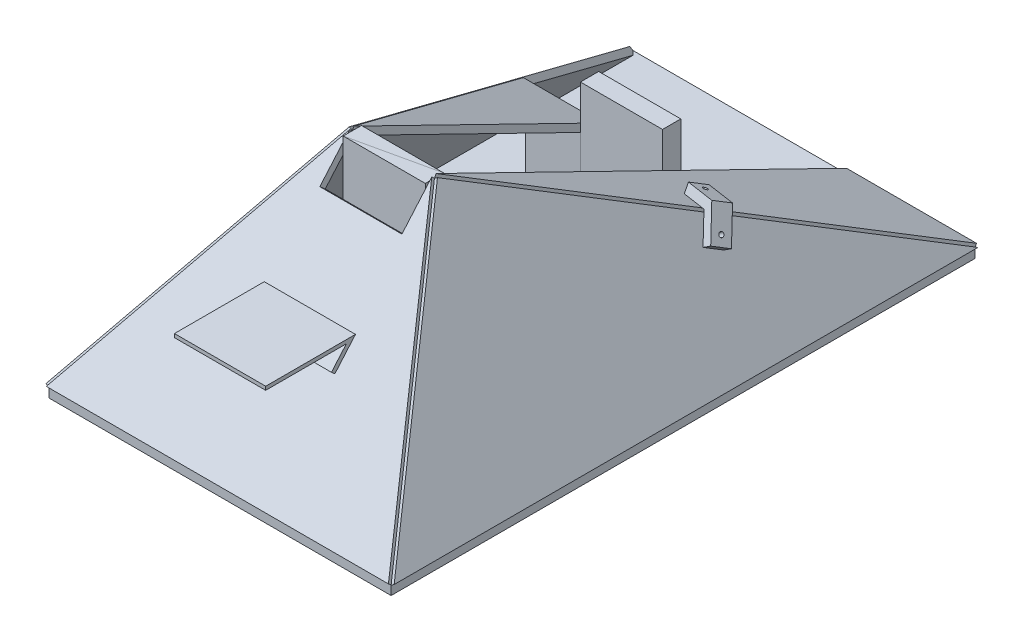
SolidWorks part; units mm, degrees
other "PlasticMountC"
other "PlasticMountB"
other "PlasticMountA"
other "PlasticMountG"
other "PlasticMountF"
other "PlasticMountE"
other "Cube Mount"
other "PlasticMountD"
other "PlasticMountH"
ref_plane "Front Plane" through (0, 0, 0) normal (0, 0, 1) x (1, 0, 0)
ref_plane "Top Plane" through (0, 0, 0) normal (0, 1, 0) x (1, 0, 0)
ref_plane "Right Plane" through (0, 0, 0) normal (1, 0, 0) x (0, 0, -1)
sketch "Sketch1" plane through (0, 0, 0) normal (0, 1, 0) x (1, 0, 0)
  line L1 (238.125, -406.4) -> (-238.125, -406.4)
  line L2 (238.125, -406.4) -> (238.125, 406.4)
  line L3 (238.125, 406.4) -> (-238.125, 406.4)
  line L4 (-238.125, -406.4) -> (-238.125, 406.4)
  line L5 (238.125, -406.4) -> (-238.125, 406.4) construction
  line L6 (238.125, 406.4) -> (-238.125, -406.4) construction
  point P0 (0, 0)
  dimension "D1" = 476.25
  dimension "D2" = 812.8
ref_plane "Plane1" through (0, 279.4, 0) normal (0, 1, 0) x (1, 0, 0)
sketch "Sketch2" plane through (0, 279.4, 0) normal (0, 1, 0) x (1, 0, 0)
  line L0 (0, 0) -> (0, -165.1) construction
  line L1 (238.125, -406.4) -> (-238.125, -406.4) construction
  line L2 (-57.15, -177.8) -> (57.15, -177.8)
  line L3 (-57.15, -177.8) -> (-57.15, -152.4)
  line L4 (-57.15, -152.4) -> (57.15, -152.4)
  line L5 (57.15, -177.8) -> (57.15, -152.4)
  line L6 (-57.15, -177.8) -> (57.15, -152.4) construction
  line L7 (-57.15, -152.4) -> (57.15, -177.8) construction
  line L8 (57.15, -165.1) -> (-57.15, -165.1) construction
  line L9 (0, 0) -> (0, 165.1) construction
  line L11 (-57.15, 152.4) -> (57.15, 152.4)
  line L12 (-57.15, 152.4) -> (-57.15, 177.8)
  line L13 (-57.15, 177.8) -> (57.15, 177.8)
  line L14 (57.15, 152.4) -> (57.15, 177.8)
  line L15 (-57.15, 152.4) -> (57.15, 177.8) construction
  line L16 (-57.15, 177.8) -> (57.15, 152.4) construction
  dimension "D1" = 114.3
  dimension "D2" = 25.4
  dimension "D3" = 228.6
  dimension "D4" = 558.8
ref_plane "Plane2" through (167.7467, 108.6541, 0) normal (0.8393, 0.5436, 0) x (0, 0, -1)
ref_plane "Plane3" through (-167.7467, 108.6541, 0) normal (-0.8393, 0.5436, 0) x (0, 0, 1)
sketch "Sketch4" plane through (167.7467, 108.6541, 0) normal (0.8393, 0.5436, 0) x (0, 0, -1)
  line L0 (-406.4, -129.4559) -> (-165.1, 203.435)
  line L2 (-165.1, 203.435) -> (406.4, -129.4559)
  line L3 (406.4, -129.4559) -> (-406.4, -129.4559)
extrude "Boss-Extrude1" add sketch "Sketch4" along normal mid plane 10
sketch "Sketch5" plane through (-167.7467, 108.6541, 0) normal (-0.8393, 0.5436, 0) x (0, 0, 1)
  line L0 (165.1, 203.435) -> (-406.4, -129.4559)
  line L1 (-406.4, -129.4559) -> (406.4, -129.4559)
  line L2 (406.4, -129.4559) -> (165.1, 203.435)
extrude "Boss-Extrude2" add sketch "Sketch5" along normal mid plane 10
extrude "Boss-Extrude3" add sketch "Sketch2" against normal up to vertex (279.4 mm away) separate body up to point (238.125, 0, 406.4)
sketch "Sketch6" plane through (0, 0, 177.8) normal (0, 0, 1) x (1, 0, 0)
  line L0 (57.15, 152.5607) -> (57.15, 177.9607)
  line L1 (57.15, 0) -> (57.15, 279.4) construction
  line L2 (57.15, 177.9607) -> (116.8977, 177.9607)
  line L3 (52.9534, 276.6818) -> (233.9284, -2.7182) construction
  line L4 (116.8977, 177.9607) -> (133.35, 152.5607)
  line L5 (133.35, 152.5607) -> (57.15, 152.5607)
  dimension "D1" = 25.4
  dimension "D2" = 76.2
extrude "Boss-Extrude4" add sketch "Sketch6" against normal blind 25.4 separate body
ref_plane "Plane4" through (133.35, 0, 0) normal (1, 0, 0) x (0, 0, -1)
hole_wizard "CBORE for 1/4 Binding Head Machine Screw1" positions "Sketch7" profile "Sketch9" counterbore size "1/4" standard "ANSI Inch" end condition through all
sketch "Sketch7" plane through (133.35, 0, 0) normal (1, 0, 0) x (0, 0, -1)
  line L0 (-177.8, 165.2607) -> (-165.1, 165.2607) construction
  line L1 (-177.8, 152.5607) -> (-177.8, 177.9607) construction
  line L2 (-165.1, 165.2607) -> (-152.4, 165.2607) construction
  line L3 (-152.4, 152.5607) -> (-152.4, 177.9607) construction
  point P0 (-165.1, 165.2607)
sketch "Sketch9" plane through (133.35, 165.2607, 165.1) normal (0, 1, 0) x (0, 0, -1)
  line L0 (0, 0) -> (0, 375.6716)
  line L1 (0, 375.6716) -> (3.3782, 375.6716)
  line L3 (3.3782, 375.6716) -> (3.3782, 54.191)
  line L4 (3.3782, 54.191) -> (7.1437, 54.191)
  line L5 (7.1437, 54.191) -> (7.1437, 0)
  line L7 (7.1437, 0) -> (0, 0)
  line L11 (0, -6.35) -> (0, 107.95) construction
  dimension "Thru Hole Dia." = 6.7564
  dimension "Thru Hole Depth" = 375.6716
  dimension "C'Bore Dia." = 14.2875
  dimension "C'Bore Depth" = 54.191
extrude "Boss-Extrude5" add sketch "Sketch1" against normal blind 12.7
sketch "Sketch10" plane through (0, 0, 177.8) normal (0, 0, 1) x (1, 0, 0)
  line L0 (182.8109, 0) -> (208.2109, 0)
  line L1 (-238.125, 0) -> (238.125, 0) construction
  line L2 (208.2109, 0) -> (208.2109, 36.986)
  line L3 (52.9534, 276.6818) -> (233.9284, -2.7182) construction
  line L4 (208.2109, 36.986) -> (182.8109, 76.2)
  line L5 (182.8109, 76.2) -> (182.8109, 0)
  dimension "D1" = 25.4
  dimension "D2" = 76.2
extrude "Boss-Extrude6" add sketch "Sketch10" along normal blind 25.4 separate body
ref_plane "Plane5" through (0, 76.2, 0) normal (0, 1, 0) x (1, 0, 0)
hole_wizard "CBORE for 1/4 Binding Head Machine Screw2" positions "Sketch11" profile "Sketch12" counterbore size "1/4" standard "ANSI Inch" end condition through all
sketch "Sketch11" plane through (0, 76.2, 0) normal (0, 1, 0) x (1, 0, 0)
  line L0 (182.8109, -190.5) -> (195.5109, -190.5) construction
  line L1 (182.8109, -203.2) -> (182.8109, -177.8) construction
  line L2 (195.5109, -190.5) -> (208.2109, -190.5) construction
  line L3 (208.2109, -203.2) -> (208.2109, -177.8) construction
  point P0 (195.5109, -190.5)
sketch "Sketch12" plane through (195.5109, 76.2, 190.5) normal (1, 0, 0) x (0, 0, 1)
  line L0 (0, 0) -> (0, 88.9)
  line L1 (0, 88.9) -> (3.3782, 88.9)
  line L3 (3.3782, 88.9) -> (3.3782, 64.191)
  line L4 (3.3782, 64.191) -> (7.1437, 64.191)
  line L5 (7.1437, 64.191) -> (7.1437, 0)
  line L7 (7.1437, 0) -> (0, 0)
  line L11 (0, -6.35) -> (0, 107.95) construction
  dimension "Thru Hole Dia." = 6.7564
  dimension "Thru Hole Depth" = 88.9
  dimension "C'Bore Dia." = 14.2875
  dimension "C'Bore Depth" = 64.191
mirror "Mirror2" about plane through (0, 0, 0) normal (1, 0, 0) of bodies 108
other "Move Face1" face at (-195.5109, 12.009, 193.8782) face at (-192.1327, 0, 190.5) parameters "D1"=6.35
ref_plane "Plane6" through (0, 201.0357, 232.7782) normal (0, 0.6536, 0.7568) x (1, 0, 0)
ref_plane "Plane7" through (0, 160.3571, -78.3968) normal (0, -0.8984, 0.4392) x (-1, 0, 0)
sketch "Sketch14" plane through (0, 201.0357, 232.7782) normal (0, 0.6536, 0.7568) x (1, 0, 0)
  line L0 (-57.15, 103.5437) -> (-238.125, -265.6311)
  line L1 (-238.125, -265.6311) -> (238.125, -265.6311)
  line L2 (238.125, -265.6311) -> (57.15, 103.5437)
  line L3 (57.15, 103.5437) -> (57.15, 40.0437)
  line L4 (57.15, 40.0437) -> (-57.15, 40.0437)
  line L5 (-57.15, 40.0437) -> (-57.15, 103.5437)
  dimension "D1" = 63.5
extrude "Boss-Extrude7" add sketch "Sketch14" along normal mid plane 10 separate body
sketch "Sketch15" plane through (0, 160.3571, -78.3968) normal (0, -0.8984, 0.4392) x (-1, 0, 0)
  line L0 (-57.15, -271.0386) -> (-57.15, 365.1034)
  line L1 (-238.125, 365.1034) -> (238.125, 365.1034) construction
  line L2 (-57.15, 365.1034) -> (-238.125, 365.1034)
  line L3 (-238.125, 365.1034) -> (-57.15, -271.0386)
extrude "Boss-Extrude8" add sketch "Sketch15" along normal mid plane 10 separate body
sketch "Sketch16" plane through (57.15, 0, 0) normal (1, 0, 0) x (0, 0, -1)
  line L0 (-177.8, 194.2135) -> (-177.8, 168.8135)
  line L1 (-177.8, 0) -> (-177.8, 279.4) construction
  line L2 (-177.8, 168.8135) -> (-254, 168.8135)
  line L3 (-402.6159, -3.2681) -> (-161.3159, 276.1319) construction
  line L4 (-254, 168.8135) -> (-232.0636, 194.2135)
  line L5 (-232.0636, 194.2135) -> (-177.8, 194.2135)
  dimension "D1" = 25.4
  dimension "D2" = 76.2
extrude "Boss-Extrude9" add sketch "Sketch16" against normal blind 25.4 separate body
ref_plane "Plane8" through (0, 0, 254) normal (0, 0, 1) x (1, 0, 0)
hole_wizard "CBORE for 1/4 Binding Head Machine Screw3" positions "Sketch19" profile "Sketch20" counterbore size "1/4" standard "ANSI Inch" end condition through all
sketch "Sketch19" plane through (0, 0, 254) normal (0, 0, 1) x (1, 0, 0)
  line L0 (44.45, 181.5135) -> (31.75, 181.5135) construction
  line L1 (31.75, 194.2135) -> (31.75, 168.8135) construction
  line L4 (44.45, 181.5135) -> (57.15, 181.5135) construction
  line L5 (57.15, 194.2135) -> (57.15, 168.8135) construction
  point P0 (44.45, 181.5135)
sketch "Sketch20" plane through (44.45, 181.5135, 254) normal (1, 0, 0) x (0, -1, 0)
  line L0 (0, 0) -> (0, 662.5961)
  line L1 (0, 662.5961) -> (3.3782, 662.5961)
  line L3 (3.3782, 662.5961) -> (3.3782, 64.191)
  line L4 (3.3782, 64.191) -> (7.1437, 64.191)
  line L5 (7.1437, 64.191) -> (7.1437, 0)
  line L7 (7.1437, 0) -> (0, 0)
  line L11 (0, -6.35) -> (0, 107.95) construction
  dimension "Thru Hole Dia." = 6.7564
  dimension "Thru Hole Depth" = 662.5961
  dimension "C'Bore Dia." = 14.2875
  dimension "C'Bore Depth" = 64.191
sketch "Sketch21" plane through (0, 0, 0) normal (1, 0, 0) x (0, 0, -1)
  line L0 (-406.4, 147.4) -> (-294.0969, 147.4)
  line L1 (-410.1841, 3.2681) -> (-168.8841, 282.6681) construction
  line L2 (-406.4, 147.4) -> (-406.4, 0) construction
  line L3 (-410.1841, 3.2681) -> (-402.6159, -3.2681) construction
  line L4 (-406.4, 147.4) -> (-406.4, 152.4)
  line L5 (-406.4, 152.4) -> (-281.3884, 152.4)
  line L7 (-281.3884, 152.4) -> (-310.0435, 119.2204)
  line L8 (-310.0435, 119.2204) -> (-314.8493, 123.3709)
  line L9 (-314.8493, 123.3709) -> (-294.0969, 147.4)
  line L10 (406.4, 0) -> (-406.4, 0) construction
  dimension "D1" = 5
  dimension "D2" = 31.75
  dimension "D3" = 6.35
  dimension "D4" = 152.4
extrude "Boss-Extrude10" add sketch "Sketch21" along normal mid plane 127 separate body
sketch "Sketch22" plane through (0, 208.4543, 241.3682) normal (0, 0.6536, 0.7568) x (1, 0, 0)
  line L0 (-63.5, -99.7219) -> (63.5, -99.7219) construction
  line L3 (-63.5, -80.6719) -> (-63.5, -112.4219) construction
  line L4 (63.5, -80.6719) -> (63.5, -112.4219) construction
  line L5 (63.5, -112.4219) -> (-63.5, -112.4219) construction
  line L6 (-35.1275, -93.8719) -> (-38.505, -99.7219)
  line L7 (-38.505, -99.7219) -> (-35.1275, -105.5719)
  line L8 (-35.1275, -105.5719) -> (-28.3725, -105.5719)
  line L9 (-28.3725, -105.5719) -> (-24.995, -99.7219)
  line L10 (-24.995, -99.7219) -> (-28.3725, -93.8719)
  line L11 (-28.3725, -93.8719) -> (-35.1275, -93.8719)
  line L12 (35.1275, -93.8719) -> (28.3725, -93.8719)
  line L13 (28.3725, -93.8719) -> (24.995, -99.7219)
  line L14 (24.995, -99.7219) -> (28.3725, -105.5719)
  line L15 (28.3725, -105.5719) -> (35.1275, -105.5719)
  line L16 (35.1275, -105.5719) -> (38.505, -99.7219)
  line L17 (38.505, -99.7219) -> (35.1275, -93.8719)
  circle A0 centre (-31.75, -99.7219) radius 5.85 construction
  circle A1 centre (31.75, -99.7219) radius 5.85 construction
  dimension "D4" = 11.7
  dimension "D1" = 12.7
  dimension "D2" = 31.75
  dimension "D3" = 31.75
extrude "Cut-Extrude1" cut sketch "Sketch22" against normal blind 3
hole_wizard "1/4 (0.25) Diameter Hole1" positions "Sketch24" profile "Sketch26" hole size "1/4" standard "ANSI Inch" end condition through all
sketch "Sketch24" plane through (0, 206.4935, 239.0977) normal (0, 0.6536, 0.7568) x (1, 0, 0)
  line L0 (-35.1275, -93.8719) -> (-28.3725, -105.5719) construction
  line L1 (24.995, -99.7219) -> (38.505, -99.7219) construction
  point P7 (-31.75, -99.7219)
  point P16 (31.75, -99.7219)
sketch "Sketch26" plane through (31.75, 131.0217, 304.2779) normal (1, 0, 0) x (0, -0.7568, 0.6536)
  line L0 (0, 0) -> (0, 631.7967)
  line L1 (0, 631.7967) -> (3.175, 631.7967)
  line L2 (3.175, 631.7967) -> (3.175, 0)
  line L5 (3.175, 0) -> (0, 0)
  line L11 (0, -6.35) -> (0, 107.95) construction
  dimension "Thru Hole Dia." = 6.35
  dimension "Thru Hole Depth" = 631.7967
sketch "Sketch27" plane through (57.15, 0, 0) normal (1, 0, 0) x (0, 0, -1)
  line L0 (-152.4, 217.9545) -> (-50.8, 217.9545)
  line L1 (-152.4, 0) -> (-152.4, 279.4) construction
  line L2 (404.2039, -4.4919) -> (-167.2961, 274.9081) construction
  line L3 (-50.8, 217.9545) -> (-102.7545, 243.3545)
  line L4 (-102.7545, 243.3545) -> (-152.4, 243.3545)
  line L5 (-152.4, 243.3545) -> (-152.4, 217.9545)
  dimension "D1" = 25.4
  dimension "D2" = 101.6
extrude "Boss-Extrude11" add sketch "Sketch27" along normal blind 25.4 separate body
ref_plane "Plane9" through (0, 0, 50.8) normal (0, 0, -1) x (-1, 0, 0)
hole_wizard "CBORE for 1/4 Binding Head Machine Screw4" positions "Sketch28" profile "Sketch30" counterbore size "1/4" standard "ANSI Inch" end condition through all
sketch "Sketch28" plane through (0, 0, 50.8) normal (0, 0, -1) x (-1, 0, 0)
  line L0 (-69.85, 243.3545) -> (-69.85, 217.9545) construction
  line L1 (-82.55, 243.3545) -> (-57.15, 243.3545) construction
  line L2 (-82.55, 217.9545) -> (-57.15, 217.9545) construction
  point P0 (-69.85, 230.6545)
sketch "Sketch30" plane through (69.85, 230.6545, 50.8) normal (1, 0, 0) x (0, 1, 0)
  line L0 (0, 0) -> (0, 359.3841)
  line L1 (0, 359.3841) -> (3.3782, 359.3841)
  line L3 (3.3782, 359.3841) -> (3.3782, 74.191)
  line L4 (3.3782, 74.191) -> (7.1437, 74.191)
  line L5 (7.1437, 74.191) -> (7.1437, 0)
  line L7 (7.1437, 0) -> (0, 0)
  line L11 (0, -6.35) -> (0, 107.95) construction
  dimension "Thru Hole Dia." = 6.7564
  dimension "Thru Hole Depth" = 359.3841
  dimension "C'Bore Dia." = 14.2875
  dimension "C'Bore Depth" = 74.191
sketch "Sketch31" plane through (57.15, 0, 0) normal (1, 0, 0) x (0, 0, -1)
  line L0 (177.8, 0) -> (177.8, 106.1945)
  line L1 (-406.4, 0) -> (406.4, 0) construction
  line L2 (404.2039, -4.4919) -> (-167.2961, 274.9081) construction
  line L3 (177.8, 106.1945) -> (152.4, 118.6122)
  line L4 (152.4, 118.6122) -> (152.4, 0)
  line L5 (152.4, 0) -> (177.8, 0)
  line L6 (177.8, 0) -> (177.8, 279.4) construction
  line L7 (152.4, 0) -> (177.8, 0) construction
extrude "Boss-Extrude12" add sketch "Sketch31" along normal blind 25.4 separate body
ref_plane "Plane10" through (0, 118.6122, 0) normal (0, 1, 0) x (1, 0, 0)
hole_wizard "CBORE for 1/4 Binding Head Machine Screw5" positions "Sketch32" profile "Sketch33" counterbore size "1/4" standard "ANSI Inch" end condition through all
sketch "Sketch32" plane through (0, 118.6122, 0) normal (0, 1, 0) x (1, 0, 0)
  line L0 (69.85, 177.8) -> (69.85, 152.4) construction
  line L1 (82.55, 177.8) -> (57.15, 177.8) construction
  line L2 (82.55, 152.4) -> (57.15, 152.4) construction
  point P8 (69.85, 165.1)
sketch "Sketch33" plane through (69.85, 118.6122, -165.1) normal (1, 0, 0) x (0, 0, 1)
  line L0 (0, 0) -> (0, 131.3122)
  line L1 (0, 131.3122) -> (3.3782, 131.3122)
  line L3 (3.3782, 131.3122) -> (3.3782, 94.191)
  line L4 (3.3782, 94.191) -> (7.1437, 94.191)
  line L5 (7.1437, 94.191) -> (7.1437, 0)
  line L7 (7.1437, 0) -> (0, 0)
  line L11 (0, -6.35) -> (0, 107.95) construction
  dimension "Thru Hole Dia." = 6.7564
  dimension "Thru Hole Depth" = 131.3122
  dimension "C'Bore Dia." = 14.2875
  dimension "C'Bore Depth" = 94.191
mirror "Mirror3" about plane through (0, 0, 0) normal (1, 0, 0) of bodies 123
other "Move Face2" face at (-69.85, 0, -161.7218) parameters "D1"=6.35
other "Move Face3" face at (-82.55, 59.3767, -165.1) parameters "D1"=50.8
ref_plane "Plane11" through (113.92, -175.8765, -359.7475) normal (0.2736, -0.4224, -0.8641) x (0, 0.8984, -0.4392)
sketch "Sketch36" plane through (113.92, -175.8765, -359.7475) normal (0.2736, -0.4224, -0.8641) x (0, 0.8984, -0.4392)
  line L0 (183.495, 93.9648) -> (183.495, 132.0648)
  line L1 (183.495, -44.9347) -> (183.495, 129.1334) construction
  line L2 (183.495, 132.0648) -> (150.2483, 150.6729)
  line L3 (-176.053, 333.3035) -> (180.937, 133.4965) construction
  line L4 (150.2483, 150.6729) -> (156.451, 161.7552)
  line L5 (156.451, 161.7552) -> (196.195, 139.5105)
  line L6 (196.195, 139.5105) -> (196.195, 93.9648)
  line L7 (196.195, 93.9648) -> (183.495, 93.9648)
  dimension "D1" = 12.7
  dimension "D2" = 38.1
extrude "Boss-Extrude13" add sketch "Sketch36" against normal blind 25.4 from offset 310 separate body offset against normal yes
hole_wizard "1/4 (0.25) Diameter Hole2" positions "Sketch39" profile "Sketch40" hole size "1/4" standard "ANSI Inch" end condition through all
sketch "Sketch39" plane through (0, 176.2585, -86.1708) normal (0, 0.8984, -0.4392) x (1, 0, 0)
  line L0 (128.2132, 60.8674) -> (115.9979, 64.3425) construction
  line L1 (112.5228, 52.1272) -> (119.4731, 76.5578) construction
  point P0 (128.2132, 60.8674)
  dimension "D1" = 12.7
sketch "Sketch40" plane through (128.2132, 149.5249, -140.8532) normal (1, 0, 0) x (0, 0.4392, 0.8984)
  line L0 (0, 0) -> (0, 386.0995)
  line L1 (0, 386.0995) -> (3.175, 386.0995)
  line L2 (3.175, 386.0995) -> (3.175, 0)
  line L5 (3.175, 0) -> (0, 0)
  line L11 (0, -6.35) -> (0, 107.95) construction
  dimension "Thru Hole Dia." = 6.35
  dimension "Thru Hole Depth" = 386.0995
hole_wizard "1/4 (0.25) Diameter Hole3" positions "Sketch41" profile "Sketch42" hole size "1/4" standard "ANSI Inch" end condition through all
sketch "Sketch41" plane through (182.6026, 118.2767, 0) normal (0.8393, 0.5436, 0) x (0, 0, -1)
  line L0 (109.8546, 2.5779) -> (116.2468, 13.552) construction
  line L1 (98.8805, 8.9701) -> (120.8286, -3.8143) construction
  point P0 (116.2468, 13.552)
  dimension "D1" = 12.7
sketch "Sketch42" plane through (175.2351, 129.651, -116.2468) normal (0, 0, 1) x (-0.5436, 0.8393, 0)
  line L0 (0, 0) -> (0, 424.3277)
  line L1 (0, 424.3277) -> (3.175, 424.3277)
  line L2 (3.175, 424.3277) -> (3.175, 0)
  line L5 (3.175, 0) -> (0, 0)
  line L11 (0, -6.35) -> (0, 107.95) construction
  dimension "Thru Hole Dia." = 6.35
  dimension "Thru Hole Depth" = 424.3277
sketch "Sketch43" plane through (0, 0, 0) normal (0, -1, 0) x (1, 0, 0)
  line L0 (57.15, 152.4) -> (133.35, 152.4) construction
  line L1 (57.15, 177.8) -> (-57.15, 177.8)
  line L2 (57.15, 177.8) -> (57.15, 152.4)
  line L3 (57.15, 152.4) -> (-57.15, 152.4)
  line L4 (-57.15, 177.8) -> (-57.15, 152.4)
  line L5 (-57.15, -152.4) -> (-57.15, -177.8) construction
extrude "Boss-Extrude15" add sketch "Sketch43" against normal up to surface (279.4 mm away) separate body up to face at (0, 279.4, -165.1)
sketch "Sketch44" plane through (0, 279.4, 0) normal (0, 1, 0) x (1, 0, 0)
  line L4 (57.15, 152.4) -> (57.15, 177.8)
  line L5 (57.15, 177.8) -> (-57.15, 177.8)
  line L6 (-57.15, 177.8) -> (-57.15, 152.4)
  line L7 (-57.15, 152.4) -> (57.15, 152.4)
  line L8 (57.15, 152.4) -> (57.15, 177.8)
  line L9 (57.15, 177.8) -> (-57.15, 177.8)
  line L10 (-57.15, 177.8) -> (-57.15, 152.4)
  line L11 (-57.15, 152.4) -> (57.15, 152.4)
  dimension "D1" = 0
extrude "Cut-Extrude2" cut sketch "Sketch44" against normal blind 100
sketch "Sketch45" plane through (0, 155.8652, -76.2008) normal (0, 0.8984, -0.4392) x (1, 0, 0)
  line L0 (-57.15, 113.0911) -> (-166.4304, 113.0911)
  line L2 (-57.15, 113.0911) -> (-57.15, -271.0386)
  line L3 (-57.15, -275.8735) -> (-57.15, -266.2036) construction
  line L4 (-57.15, -271.0386) -> (-166.4304, 113.0911)
  line L5 (-61.3466, -272.2324) -> (-242.3216, 363.9095) construction
extrude "Boss-Extrude16" add sketch "Sketch45" along normal blind 10 separate body
